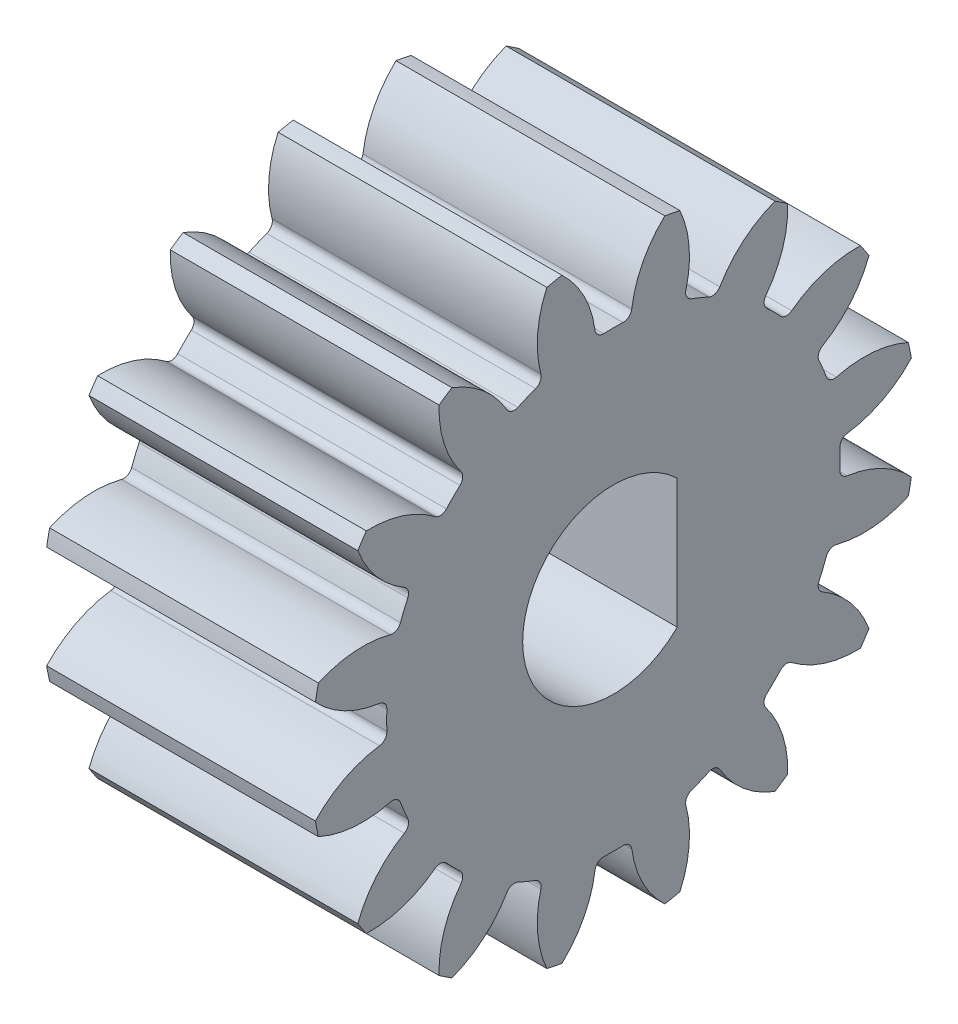
SolidWorks part; units mm, degrees
other "GearB1" parameters "Num_teeth"=16
material "Nylon 101"
ref_plane "Plane1" through (0, 0, 0) normal (0, 0, 1) x (1, 0, 0)
ref_plane "Plane2" through (0, 0, 0) normal (0, 1, 0) x (1, 0, 0)
ref_plane "Plane3" through (0, 0, 0) normal (1, 0, 0) x (0, 0, -1)
sketch "BasProSke" plane through (0, 0, 0) normal (0, 1, 0) x (1, 0, 0)
  line L0 (-10, 0) -> (60, 0) construction
  line L1 (0, 0) -> (0, 4.5)
  line L2 (0, 0) -> (4, 0)
  line L3 (4, 0) -> (4, 4.5)
  line L4 (4, 4.5) -> (0, 4.5)
  dimension "Diameter" = 9
  dimension "Thickness" = 4
revolve "Base-Revolve" add sketch "BasProSke" angle 360 about L0
sketch "TooCutSke" plane through (0, 0, 0) normal (1, 0, 0) x (0, 0, -1)
  line L1 (0, 0) -> (0, 107) construction
  line L2 (0, 0) -> (-0.4253, 3.9773) construction
  line L3 (0, 0) -> (-1.5544, 7.8146) construction
  line L4 (-0.4253, 3.9773) -> (-0.7772, 3.9073) construction
  arc A0 (0.2619, 3.3638) -> (-0.2619, 3.3638) centre (0, 0) ccw
  arc A1 (0.7886, 4.4562) -> (-0.7886, 4.4562) centre (0, 0) ccw
  circle A2 centre (0, 0) radius 4 construction
  circle A3 centre (0, 0) radius 3.7588 construction
  arc A4 (-0.2619, 3.3638) -> (-0.7886, 4.4562) centre (-1.8589, 3.2669) ccw
  arc A5 (0.7886, 4.4562) -> (0.2619, 3.3638) centre (1.8589, 3.2669) ccw
  dimension "Root_dia" = 6.748
  dimension "Overcut_dia" = 9.0508
  dimension "Pitch_dia" = 8
  dimension "Base_dia" = 7.5175
  dimension "Flank_rad" = 1.6
  dimension "Half_ang" = 11.25
  dimension "Half_CT" = 0.3588
extrude "ToothCut" cut sketch "TooCutSke" along normal through all
fillet "RootFillets" radius 0.126 2 edges at (2, 3.3638, -0.2619) (2, 3.3638, 0.2619)
pattern_circular "TeethCuts" count 16 over 360 about axis through (0, 0, 0) along (1, 0, 0) of "ToothCut", "RootFillets"
sketch "ShaftHoleSke" plane through (4, 0, 0) normal (1, 0, 0) x (0, 0, -1)
  line L0 (0.95, -0.9592) -> (0.95, 0.9592)
  arc A0 (0.95, 0.9592) -> (0.95, -0.9592) centre (0, 0) ccw
  dimension "D1" = 1.35
  dimension "D2" = 0.95
extrude "ShaftHole" cut sketch "ShaftHoleSke" against normal through all
sketch "ScrewHoleSke" plane through (0, 0, -0.95) normal (0, 0, 1) x (1, 0, 0)
  line L0 (0, 0) -> (4, 0) construction
  line L1 (0, 0.143) -> (0, -0.143) construction
  line L2 (4, -0.143) -> (4, 0.143) construction
  circle A0 centre (2, 0) radius 0.425
  point P11 (2, 0)
  dimension "D1" = 0.85
extrude "ScrewHole" cut sketch "ScrewHoleSke" against normal through all
equation "\"OAL@HoldingSke\" = \"Thickness@HoldingSke\""
equation "\"MHD@HoldingSke\" = (\"Num_teeth@HoldingSke\" + 2) / \"Pitch@HoldingSke\" - 2 * (\"Addendum_fac@HoldingSke\" + \"Dedendum_fac@HoldingSke\")  / \"Pitch@HoldingSke\" - \"Dedendum_add@HoldingSke\" * 2"
equation "\"MBD@HoldingSke\" = (\"Num_teeth@HoldingSke\" + 2) / \"Pitch@HoldingSke\" - 2 * (\"Addendum_fac@HoldingSke\" + \"Dedendum_fac@HoldingSke\")  / \"Pitch@HoldingSke\" - \"Dedendum_add@HoldingSke\" * 2 - 0.002 * 25.4"
equation "\"MHD@HoldingSke\" = ((sgn( \"MHD@HoldingSke\" - \"Hub_dia@HoldingSke\" )-1)*( \"MHD@HoldingSke\" - \"Hub_dia@HoldingSke\" ))/-2+ \"Hub_dia@HoldingSke\""
equation "\"Num_teeth@TeethCuts\" = int( \"Show_teeth@HoldingSke\" ) + 1"
equation "\"Num_teeth@TeethCuts\" = ((sgn( \"Num_teeth@TeethCuts\" - \"Num_teeth@HoldingSke\" )-1)*( \"Num_teeth@TeethCuts\" - \"Num_teeth@HoldingSke\" ))/-2+ \"Num_teeth@HoldingSke\""
